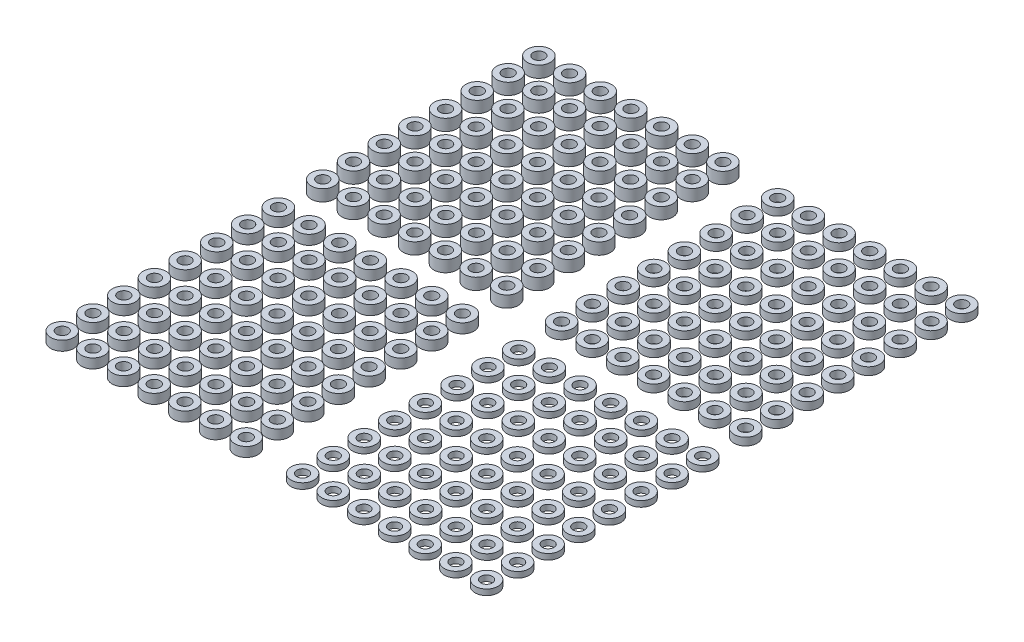
SolidWorks part; units mm, degrees
ref_plane "前视基准面" through (0, 0, 0) normal (0, 0, 1) x (1, 0, 0)
ref_plane "上视基准面" through (0, 0, 0) normal (0, 1, 0) x (1, 0, 0)
ref_plane "右视基准面" through (0, 0, 0) normal (1, 0, 0) x (0, 0, -1)
sketch "草图1" plane through (0, 0, 0) normal (0, 1, 0) x (1, 0, 0)
  circle A0 centre (0, 0) radius 3
  circle A1 centre (0, 0) radius 1.5
  circle A2 centre (8, 0) radius 3
  circle A3 centre (8, 0) radius 1.5
  circle A4 centre (16, 0) radius 3
  circle A5 centre (16, 0) radius 1.5
  circle A6 centre (24, 0) radius 3
  circle A7 centre (24, 0) radius 1.5
  circle A8 centre (32, 0) radius 3
  circle A9 centre (32, 0) radius 1.5
  circle A10 centre (40, 0) radius 3
  circle A11 centre (40, 0) radius 1.5
  circle A12 centre (48, 0) radius 3
  circle A13 centre (48, 0) radius 1.5
  circle A14 centre (0.01, 8.0075) radius 3
  circle A15 centre (0.01, 8.0075) radius 1.5
  circle A16 centre (8.0961, 8.0075) radius 3
  circle A17 centre (8.0961, 8.0075) radius 1.5
  circle A18 centre (16.0961, 8.0075) radius 3
  circle A19 centre (16.0961, 8.0075) radius 1.5
  circle A20 centre (24.0961, 8.0075) radius 3
  circle A21 centre (24.0961, 8.0075) radius 1.5
  circle A22 centre (32.0961, 8.0075) radius 3
  circle A23 centre (32.0961, 8.0075) radius 1.5
  circle A24 centre (40.0961, 8.0075) radius 3
  circle A25 centre (40.0961, 8.0075) radius 1.5
  circle A26 centre (48.0961, 8.0075) radius 3
  circle A27 centre (48.0961, 8.0075) radius 1.5
  circle A28 centre (0.0099, 16.0471) radius 3
  circle A29 centre (0.0099, 16.0471) radius 1.5
  circle A30 centre (8.0099, 16.0471) radius 3
  circle A31 centre (8.0099, 16.0471) radius 1.5
  circle A32 centre (16.0099, 16.0471) radius 3
  circle A33 centre (16.0099, 16.0471) radius 1.5
  circle A34 centre (24.0099, 16.0471) radius 3
  circle A35 centre (24.0099, 16.0471) radius 1.5
  circle A36 centre (32.0099, 16.0471) radius 3
  circle A37 centre (32.0099, 16.0471) radius 1.5
  circle A38 centre (40.0099, 16.0471) radius 3
  circle A39 centre (40.0099, 16.0471) radius 1.5
  circle A40 centre (48.0099, 16.0471) radius 3
  circle A41 centre (48.0099, 16.0471) radius 1.5
  circle A42 centre (0.0598, 23.9919) radius 3
  circle A43 centre (0.0598, 23.9919) radius 1.5
  circle A44 centre (8.0598, 23.9919) radius 3
  circle A45 centre (8.0598, 23.9919) radius 1.5
  circle A46 centre (16.0598, 23.9919) radius 3
  circle A47 centre (16.0598, 23.9919) radius 1.5
  circle A48 centre (24.0598, 23.9919) radius 3
  circle A49 centre (24.0598, 23.9919) radius 1.5
  circle A50 centre (32.0598, 23.9919) radius 3
  circle A51 centre (32.0598, 23.9919) radius 1.5
  circle A52 centre (40.0598, 23.9919) radius 3
  circle A53 centre (40.0598, 23.9919) radius 1.5
  circle A54 centre (48.0598, 23.9919) radius 3
  circle A55 centre (48.0598, 23.9919) radius 1.5
  circle A56 centre (0.1119, 31.9298) radius 3
  circle A57 centre (0.1119, 31.9298) radius 1.5
  circle A58 centre (8.1119, 31.9298) radius 3
  circle A59 centre (8.1119, 31.9298) radius 1.5
  circle A60 centre (16.1119, 31.9298) radius 3
  circle A61 centre (16.1119, 31.9298) radius 1.5
  circle A62 centre (24.1119, 31.9298) radius 3
  circle A63 centre (24.1119, 31.9298) radius 1.5
  circle A64 centre (32.1119, 31.9298) radius 3
  circle A65 centre (32.1119, 31.9298) radius 1.5
  circle A66 centre (40.1119, 31.9298) radius 3
  circle A67 centre (40.1119, 31.9298) radius 1.5
  circle A68 centre (48.1119, 31.9298) radius 3
  circle A69 centre (48.1119, 31.9298) radius 1.5
  circle A70 centre (0.1864, 40.1126) radius 3
  circle A71 centre (0.1864, 40.1126) radius 1.5
  circle A72 centre (8.1864, 40.1126) radius 3
  circle A73 centre (8.1864, 40.1126) radius 1.5
  circle A74 centre (16.1864, 40.1126) radius 3
  circle A75 centre (16.1864, 40.1126) radius 1.5
  circle A76 centre (24.1864, 40.1126) radius 3
  circle A77 centre (24.1864, 40.1126) radius 1.5
  circle A78 centre (32.1864, 40.1126) radius 3
  circle A79 centre (32.1864, 40.1126) radius 1.5
  circle A80 centre (40.1864, 40.1126) radius 3
  circle A81 centre (40.1864, 40.1126) radius 1.5
  circle A82 centre (48.1864, 40.1126) radius 3
  circle A83 centre (48.1864, 40.1126) radius 1.5
  circle A84 centre (0.1363, 48.2281) radius 3
  circle A85 centre (0.1363, 48.2281) radius 1.5
  circle A86 centre (8.1363, 48.2281) radius 3
  circle A87 centre (8.1363, 48.2281) radius 1.5
  circle A88 centre (16.1363, 48.2281) radius 3
  circle A89 centre (16.1363, 48.2281) radius 1.5
  circle A90 centre (24.1363, 48.2281) radius 3
  circle A91 centre (24.1363, 48.2281) radius 1.5
  circle A92 centre (32.1363, 48.2281) radius 3
  circle A93 centre (32.1363, 48.2281) radius 1.5
  circle A94 centre (40.1363, 48.2281) radius 3
  circle A95 centre (40.1363, 48.2281) radius 1.5
  circle A96 centre (48.1363, 48.2281) radius 3
  circle A97 centre (48.1363, 48.2281) radius 1.5
  circle A98 centre (0.2651, 56.1121) radius 3
  circle A99 centre (0.2651, 56.1121) radius 1.5
  circle A100 centre (8.2651, 56.1121) radius 3
  circle A101 centre (8.2651, 56.1121) radius 1.5
  circle A102 centre (16.2651, 56.1121) radius 3
  circle A103 centre (16.2651, 56.1121) radius 1.5
  circle A104 centre (24.2651, 56.1121) radius 3
  circle A105 centre (24.2651, 56.1121) radius 1.5
  circle A106 centre (32.2651, 56.1121) radius 3
  circle A107 centre (32.2651, 56.1121) radius 1.5
  circle A108 centre (40.2651, 56.1121) radius 3
  circle A109 centre (40.2651, 56.1121) radius 1.5
  circle A110 centre (48.2651, 56.1121) radius 3
  circle A111 centre (48.2651, 56.1121) radius 1.5
  point P30 (0, 0)
  point P47 (0, 0)
extrude "凸台-拉伸1" add sketch "草图1" along normal blind 3
sketch "草图3" plane through (0, 0, 0) normal (0, 1, 0) x (1, 0, 0)
  circle A0 centre (62.2791, 0.0173) radius 3
  circle A1 centre (62.2791, 0.0173) radius 1.5
  circle A2 centre (70.2791, 0.0173) radius 3
  circle A3 centre (70.2791, 0.0173) radius 1.5
  circle A4 centre (78.2791, 0.0173) radius 3
  circle A5 centre (78.2791, 0.0173) radius 1.5
  circle A6 centre (86.2791, 0.0173) radius 3
  circle A7 centre (86.2791, 0.0173) radius 1.5
  circle A8 centre (94.2791, 0.0173) radius 3
  circle A9 centre (94.2791, 0.0173) radius 1.5
  circle A10 centre (102.2791, 0.0173) radius 3
  circle A11 centre (102.2791, 0.0173) radius 1.5
  circle A12 centre (110.2791, 0.0173) radius 3
  circle A13 centre (110.2791, 0.0173) radius 1.5
  circle A14 centre (62.2892, 8.0248) radius 3
  circle A15 centre (62.2892, 8.0248) radius 1.5
  circle A16 centre (70.3752, 8.0248) radius 3
  circle A17 centre (70.3752, 8.0248) radius 1.5
  circle A18 centre (78.3752, 8.0248) radius 3
  circle A19 centre (78.3752, 8.0248) radius 1.5
  circle A20 centre (86.3752, 8.0248) radius 3
  circle A21 centre (86.3752, 8.0248) radius 1.5
  circle A22 centre (94.3752, 8.0248) radius 3
  circle A23 centre (94.3752, 8.0248) radius 1.5
  circle A24 centre (102.3752, 8.0248) radius 3
  circle A25 centre (102.3752, 8.0248) radius 1.5
  circle A26 centre (110.3752, 8.0248) radius 3
  circle A27 centre (110.3752, 8.0248) radius 1.5
  circle A28 centre (62.289, 16.0645) radius 3
  circle A29 centre (62.289, 16.0645) radius 1.5
  circle A30 centre (70.289, 16.0645) radius 3
  circle A31 centre (70.289, 16.0645) radius 1.5
  circle A32 centre (78.289, 16.0645) radius 3
  circle A33 centre (78.289, 16.0645) radius 1.5
  circle A34 centre (86.289, 16.0645) radius 3
  circle A35 centre (86.289, 16.0645) radius 1.5
  circle A36 centre (94.289, 16.0645) radius 3
  circle A37 centre (94.289, 16.0645) radius 1.5
  circle A38 centre (102.289, 16.0645) radius 3
  circle A39 centre (102.289, 16.0645) radius 1.5
  circle A40 centre (110.289, 16.0645) radius 3
  circle A41 centre (110.289, 16.0645) radius 1.5
  circle A42 centre (62.3389, 24.0092) radius 3
  circle A43 centre (62.3389, 24.0092) radius 1.5
  circle A44 centre (70.3389, 24.0092) radius 3
  circle A45 centre (70.3389, 24.0092) radius 1.5
  circle A46 centre (78.3389, 24.0092) radius 3
  circle A47 centre (78.3389, 24.0092) radius 1.5
  circle A48 centre (86.3389, 24.0092) radius 3
  circle A49 centre (86.3389, 24.0092) radius 1.5
  circle A50 centre (94.3389, 24.0092) radius 3
  circle A51 centre (94.3389, 24.0092) radius 1.5
  circle A52 centre (102.3389, 24.0092) radius 3
  circle A53 centre (102.3389, 24.0092) radius 1.5
  circle A54 centre (110.3389, 24.0092) radius 3
  circle A55 centre (110.3389, 24.0092) radius 1.5
  circle A56 centre (62.391, 31.9471) radius 3
  circle A57 centre (62.391, 31.9471) radius 1.5
  circle A58 centre (70.391, 31.9471) radius 3
  circle A59 centre (70.391, 31.9471) radius 1.5
  circle A60 centre (78.391, 31.9471) radius 3
  circle A61 centre (78.391, 31.9471) radius 1.5
  circle A62 centre (86.391, 31.9471) radius 3
  circle A63 centre (86.391, 31.9471) radius 1.5
  circle A64 centre (94.391, 31.9471) radius 3
  circle A65 centre (94.391, 31.9471) radius 1.5
  circle A66 centre (102.391, 31.9471) radius 3
  circle A67 centre (102.391, 31.9471) radius 1.5
  circle A68 centre (110.391, 31.9471) radius 3
  circle A69 centre (110.391, 31.9471) radius 1.5
  circle A70 centre (62.4655, 40.1299) radius 3
  circle A71 centre (62.4655, 40.1299) radius 1.5
  circle A72 centre (70.4655, 40.1299) radius 3
  circle A73 centre (70.4655, 40.1299) radius 1.5
  circle A74 centre (78.4655, 40.1299) radius 3
  circle A75 centre (78.4655, 40.1299) radius 1.5
  circle A76 centre (86.4655, 40.1299) radius 3
  circle A77 centre (86.4655, 40.1299) radius 1.5
  circle A78 centre (94.4655, 40.1299) radius 3
  circle A79 centre (94.4655, 40.1299) radius 1.5
  circle A80 centre (102.4655, 40.1299) radius 3
  circle A81 centre (102.4655, 40.1299) radius 1.5
  circle A82 centre (110.4655, 40.1299) radius 3
  circle A83 centre (110.4655, 40.1299) radius 1.5
  circle A84 centre (62.4154, 48.2454) radius 3
  circle A85 centre (62.4154, 48.2454) radius 1.5
  circle A86 centre (70.4154, 48.2454) radius 3
  circle A87 centre (70.4154, 48.2454) radius 1.5
  circle A88 centre (78.4154, 48.2454) radius 3
  circle A89 centre (78.4154, 48.2454) radius 1.5
  circle A90 centre (86.4154, 48.2454) radius 3
  circle A91 centre (86.4154, 48.2454) radius 1.5
  circle A92 centre (94.4154, 48.2454) radius 3
  circle A93 centre (94.4154, 48.2454) radius 1.5
  circle A94 centre (102.4154, 48.2454) radius 3
  circle A95 centre (102.4154, 48.2454) radius 1.5
  circle A96 centre (110.4154, 48.2454) radius 3
  circle A97 centre (110.4154, 48.2454) radius 1.5
  circle A98 centre (62.5442, 56.1294) radius 3
  circle A99 centre (62.5442, 56.1294) radius 1.5
  circle A100 centre (70.5442, 56.1294) radius 3
  circle A101 centre (70.5442, 56.1294) radius 1.5
  circle A102 centre (78.5442, 56.1294) radius 3
  circle A103 centre (78.5442, 56.1294) radius 1.5
  circle A104 centre (86.5442, 56.1294) radius 3
  circle A105 centre (86.5442, 56.1294) radius 1.5
  circle A106 centre (94.5442, 56.1294) radius 3
  circle A107 centre (94.5442, 56.1294) radius 1.5
  circle A108 centre (102.5442, 56.1294) radius 3
  circle A109 centre (102.5442, 56.1294) radius 1.5
  circle A110 centre (110.5442, 56.1294) radius 3
  circle A111 centre (110.5442, 56.1294) radius 1.5
extrude "凸台-拉伸2" add sketch "草图3" along normal blind 2 separate body
sketch "草图5" plane through (0, 0, 0) normal (0, 1, 0) x (1, 0, 0)
  circle A0 centre (-0.2512, -67.7002) radius 3
  circle A1 centre (-0.2512, -67.7002) radius 1.5
  circle A2 centre (7.7488, -67.7002) radius 3
  circle A3 centre (7.7488, -67.7002) radius 1.5
  circle A4 centre (15.7488, -67.7002) radius 3
  circle A5 centre (15.7488, -67.7002) radius 1.5
  circle A6 centre (23.7488, -67.7002) radius 3
  circle A7 centre (23.7488, -67.7002) radius 1.5
  circle A8 centre (31.7488, -67.7002) radius 3
  circle A9 centre (31.7488, -67.7002) radius 1.5
  circle A10 centre (39.7488, -67.7002) radius 3
  circle A11 centre (39.7488, -67.7002) radius 1.5
  circle A12 centre (47.7488, -67.7002) radius 3
  circle A13 centre (47.7488, -67.7002) radius 1.5
  circle A14 centre (-0.2412, -59.6927) radius 3
  circle A15 centre (-0.2412, -59.6927) radius 1.5
  circle A16 centre (7.8448, -59.6927) radius 3
  circle A17 centre (7.8448, -59.6927) radius 1.5
  circle A18 centre (15.8448, -59.6927) radius 3
  circle A19 centre (15.8448, -59.6927) radius 1.5
  circle A20 centre (23.8448, -59.6927) radius 3
  circle A21 centre (23.8448, -59.6927) radius 1.5
  circle A22 centre (31.8448, -59.6927) radius 3
  circle A23 centre (31.8448, -59.6927) radius 1.5
  circle A24 centre (39.8448, -59.6927) radius 3
  circle A25 centre (39.8448, -59.6927) radius 1.5
  circle A26 centre (47.8448, -59.6927) radius 3
  circle A27 centre (47.8448, -59.6927) radius 1.5
  circle A28 centre (-0.2413, -51.6531) radius 3
  circle A29 centre (-0.2413, -51.6531) radius 1.5
  circle A30 centre (7.7587, -51.6531) radius 3
  circle A31 centre (7.7587, -51.6531) radius 1.5
  circle A32 centre (15.7587, -51.6531) radius 3
  circle A33 centre (15.7587, -51.6531) radius 1.5
  circle A34 centre (23.7587, -51.6531) radius 3
  circle A35 centre (23.7587, -51.6531) radius 1.5
  circle A36 centre (31.7587, -51.6531) radius 3
  circle A37 centre (31.7587, -51.6531) radius 1.5
  circle A38 centre (39.7587, -51.6531) radius 3
  circle A39 centre (39.7587, -51.6531) radius 1.5
  circle A40 centre (47.7587, -51.6531) radius 3
  circle A41 centre (47.7587, -51.6531) radius 1.5
  circle A42 centre (-0.1914, -43.7083) radius 3
  circle A43 centre (-0.1914, -43.7083) radius 1.5
  circle A44 centre (7.8086, -43.7083) radius 3
  circle A45 centre (7.8086, -43.7083) radius 1.5
  circle A46 centre (15.8086, -43.7083) radius 3
  circle A47 centre (15.8086, -43.7083) radius 1.5
  circle A48 centre (23.8086, -43.7083) radius 3
  circle A49 centre (23.8086, -43.7083) radius 1.5
  circle A50 centre (31.8086, -43.7083) radius 3
  circle A51 centre (31.8086, -43.7083) radius 1.5
  circle A52 centre (39.8086, -43.7083) radius 3
  circle A53 centre (39.8086, -43.7083) radius 1.5
  circle A54 centre (47.8086, -43.7083) radius 3
  circle A55 centre (47.8086, -43.7083) radius 1.5
  circle A56 centre (-0.1394, -35.7705) radius 3
  circle A57 centre (-0.1394, -35.7705) radius 1.5
  circle A58 centre (7.8606, -35.7705) radius 3
  circle A59 centre (7.8606, -35.7705) radius 1.5
  circle A60 centre (15.8606, -35.7705) radius 3
  circle A61 centre (15.8606, -35.7705) radius 1.5
  circle A62 centre (23.8606, -35.7705) radius 3
  circle A63 centre (23.8606, -35.7705) radius 1.5
  circle A64 centre (31.8606, -35.7705) radius 3
  circle A65 centre (31.8606, -35.7705) radius 1.5
  circle A66 centre (39.8606, -35.7705) radius 3
  circle A67 centre (39.8606, -35.7705) radius 1.5
  circle A68 centre (47.8606, -35.7705) radius 3
  circle A69 centre (47.8606, -35.7705) radius 1.5
  circle A70 centre (-0.0649, -27.5877) radius 3
  circle A71 centre (-0.0649, -27.5877) radius 1.5
  circle A72 centre (7.9351, -27.5877) radius 3
  circle A73 centre (7.9351, -27.5877) radius 1.5
  circle A74 centre (15.9351, -27.5877) radius 3
  circle A75 centre (15.9351, -27.5877) radius 1.5
  circle A76 centre (23.9351, -27.5877) radius 3
  circle A77 centre (23.9351, -27.5877) radius 1.5
  circle A78 centre (31.9351, -27.5877) radius 3
  circle A79 centre (31.9351, -27.5877) radius 1.5
  circle A80 centre (39.9351, -27.5877) radius 3
  circle A81 centre (39.9351, -27.5877) radius 1.5
  circle A82 centre (47.9351, -27.5877) radius 3
  circle A83 centre (47.9351, -27.5877) radius 1.5
  circle A84 centre (-0.115, -19.4721) radius 3
  circle A85 centre (-0.115, -19.4721) radius 1.5
  circle A86 centre (7.885, -19.4721) radius 3
  circle A87 centre (7.885, -19.4721) radius 1.5
  circle A88 centre (15.885, -19.4721) radius 3
  circle A89 centre (15.885, -19.4721) radius 1.5
  circle A90 centre (23.885, -19.4721) radius 3
  circle A91 centre (23.885, -19.4721) radius 1.5
  circle A92 centre (31.885, -19.4721) radius 3
  circle A93 centre (31.885, -19.4721) radius 1.5
  circle A94 centre (39.885, -19.4721) radius 3
  circle A95 centre (39.885, -19.4721) radius 1.5
  circle A96 centre (47.885, -19.4721) radius 3
  circle A97 centre (47.885, -19.4721) radius 1.5
  circle A98 centre (0.0138, -11.5881) radius 3
  circle A99 centre (0.0138, -11.5881) radius 1.5
  circle A100 centre (8.0138, -11.5881) radius 3
  circle A101 centre (8.0138, -11.5881) radius 1.5
  circle A102 centre (16.0138, -11.5881) radius 3
  circle A103 centre (16.0138, -11.5881) radius 1.5
  circle A104 centre (24.0138, -11.5881) radius 3
  circle A105 centre (24.0138, -11.5881) radius 1.5
  circle A106 centre (32.0138, -11.5881) radius 3
  circle A107 centre (32.0138, -11.5881) radius 1.5
  circle A108 centre (40.0138, -11.5881) radius 3
  circle A109 centre (40.0138, -11.5881) radius 1.5
  circle A110 centre (48.0138, -11.5881) radius 3
  circle A111 centre (48.0138, -11.5881) radius 1.5
extrude "凸台-拉伸3" add sketch "草图5" along normal blind 2.5 separate body
sketch "草图6" plane through (0, 0, 0) normal (0, 1, 0) x (1, 0, 0)
  circle A0 centre (62.2918, -67.5582) radius 3
  circle A1 centre (62.2918, -67.5582) radius 1.5
  circle A2 centre (70.2918, -67.5582) radius 3
  circle A3 centre (70.2918, -67.5582) radius 1.5
  circle A4 centre (78.2918, -67.5582) radius 3
  circle A5 centre (78.2918, -67.5582) radius 1.5
  circle A6 centre (86.2918, -67.5582) radius 3
  circle A7 centre (86.2918, -67.5582) radius 1.5
  circle A8 centre (94.2918, -67.5582) radius 3
  circle A9 centre (94.2918, -67.5582) radius 1.5
  circle A10 centre (102.2918, -67.5582) radius 3
  circle A11 centre (102.2918, -67.5582) radius 1.5
  circle A12 centre (110.2918, -67.5582) radius 3
  circle A13 centre (110.2918, -67.5582) radius 1.5
  circle A14 centre (62.3018, -59.5508) radius 3
  circle A15 centre (62.3018, -59.5508) radius 1.5
  circle A16 centre (70.3878, -59.5508) radius 3
  circle A17 centre (70.3878, -59.5508) radius 1.5
  circle A18 centre (78.3878, -59.5508) radius 3
  circle A19 centre (78.3878, -59.5508) radius 1.5
  circle A20 centre (86.3878, -59.5508) radius 3
  circle A21 centre (86.3878, -59.5508) radius 1.5
  circle A22 centre (94.3878, -59.5508) radius 3
  circle A23 centre (94.3878, -59.5508) radius 1.5
  circle A24 centre (102.3878, -59.5508) radius 3
  circle A25 centre (102.3878, -59.5508) radius 1.5
  circle A26 centre (110.3878, -59.5508) radius 3
  circle A27 centre (110.3878, -59.5508) radius 1.5
  circle A28 centre (62.3017, -51.5111) radius 3
  circle A29 centre (62.3017, -51.5111) radius 1.5
  circle A30 centre (70.3017, -51.5111) radius 3
  circle A31 centre (70.3017, -51.5111) radius 1.5
  circle A32 centre (78.3017, -51.5111) radius 3
  circle A33 centre (78.3017, -51.5111) radius 1.5
  circle A34 centre (86.3017, -51.5111) radius 3
  circle A35 centre (86.3017, -51.5111) radius 1.5
  circle A36 centre (94.3017, -51.5111) radius 3
  circle A37 centre (94.3017, -51.5111) radius 1.5
  circle A38 centre (102.3017, -51.5111) radius 3
  circle A39 centre (102.3017, -51.5111) radius 1.5
  circle A40 centre (110.3017, -51.5111) radius 3
  circle A41 centre (110.3017, -51.5111) radius 1.5
  circle A42 centre (62.3516, -43.5664) radius 3
  circle A43 centre (62.3516, -43.5664) radius 1.5
  circle A44 centre (70.3516, -43.5664) radius 3
  circle A45 centre (70.3516, -43.5664) radius 1.5
  circle A46 centre (78.3516, -43.5664) radius 3
  circle A47 centre (78.3516, -43.5664) radius 1.5
  circle A48 centre (86.3516, -43.5664) radius 3
  circle A49 centre (86.3516, -43.5664) radius 1.5
  circle A50 centre (94.3516, -43.5664) radius 3
  circle A51 centre (94.3516, -43.5664) radius 1.5
  circle A52 centre (102.3516, -43.5664) radius 3
  circle A53 centre (102.3516, -43.5664) radius 1.5
  circle A54 centre (110.3516, -43.5664) radius 3
  circle A55 centre (110.3516, -43.5664) radius 1.5
  circle A56 centre (62.4036, -35.6285) radius 3
  circle A57 centre (62.4036, -35.6285) radius 1.5
  circle A58 centre (70.4036, -35.6285) radius 3
  circle A59 centre (70.4036, -35.6285) radius 1.5
  circle A60 centre (78.4036, -35.6285) radius 3
  circle A61 centre (78.4036, -35.6285) radius 1.5
  circle A62 centre (86.4036, -35.6285) radius 3
  circle A63 centre (86.4036, -35.6285) radius 1.5
  circle A64 centre (94.4036, -35.6285) radius 3
  circle A65 centre (94.4036, -35.6285) radius 1.5
  circle A66 centre (102.4036, -35.6285) radius 3
  circle A67 centre (102.4036, -35.6285) radius 1.5
  circle A68 centre (110.4036, -35.6285) radius 3
  circle A69 centre (110.4036, -35.6285) radius 1.5
  circle A70 centre (62.4781, -27.4457) radius 3
  circle A71 centre (62.4781, -27.4457) radius 1.5
  circle A72 centre (70.4781, -27.4457) radius 3
  circle A73 centre (70.4781, -27.4457) radius 1.5
  circle A74 centre (78.4781, -27.4457) radius 3
  circle A75 centre (78.4781, -27.4457) radius 1.5
  circle A76 centre (86.4781, -27.4457) radius 3
  circle A77 centre (86.4781, -27.4457) radius 1.5
  circle A78 centre (94.4781, -27.4457) radius 3
  circle A79 centre (94.4781, -27.4457) radius 1.5
  circle A80 centre (102.4781, -27.4457) radius 3
  circle A81 centre (102.4781, -27.4457) radius 1.5
  circle A82 centre (110.4781, -27.4457) radius 3
  circle A83 centre (110.4781, -27.4457) radius 1.5
  circle A84 centre (62.428, -19.3302) radius 3
  circle A85 centre (62.428, -19.3302) radius 1.5
  circle A86 centre (70.428, -19.3302) radius 3
  circle A87 centre (70.428, -19.3302) radius 1.5
  circle A88 centre (78.428, -19.3302) radius 3
  circle A89 centre (78.428, -19.3302) radius 1.5
  circle A90 centre (86.428, -19.3302) radius 3
  circle A91 centre (86.428, -19.3302) radius 1.5
  circle A92 centre (94.428, -19.3302) radius 3
  circle A93 centre (94.428, -19.3302) radius 1.5
  circle A94 centre (102.428, -19.3302) radius 3
  circle A95 centre (102.428, -19.3302) radius 1.5
  circle A96 centre (110.428, -19.3302) radius 3
  circle A97 centre (110.428, -19.3302) radius 1.5
  circle A98 centre (62.5568, -11.4462) radius 3
  circle A99 centre (62.5568, -11.4462) radius 1.5
  circle A100 centre (70.5568, -11.4462) radius 3
  circle A101 centre (70.5568, -11.4462) radius 1.5
  circle A102 centre (78.5568, -11.4462) radius 3
  circle A103 centre (78.5568, -11.4462) radius 1.5
  circle A104 centre (86.5568, -11.4462) radius 3
  circle A105 centre (86.5568, -11.4462) radius 1.5
  circle A106 centre (94.5568, -11.4462) radius 3
  circle A107 centre (94.5568, -11.4462) radius 1.5
  circle A108 centre (102.5568, -11.4462) radius 3
  circle A109 centre (102.5568, -11.4462) radius 1.5
  circle A110 centre (110.5568, -11.4462) radius 3
  circle A111 centre (110.5568, -11.4462) radius 1.5
extrude "凸台-拉伸4" add sketch "草图6" along normal blind 1.5 separate body
